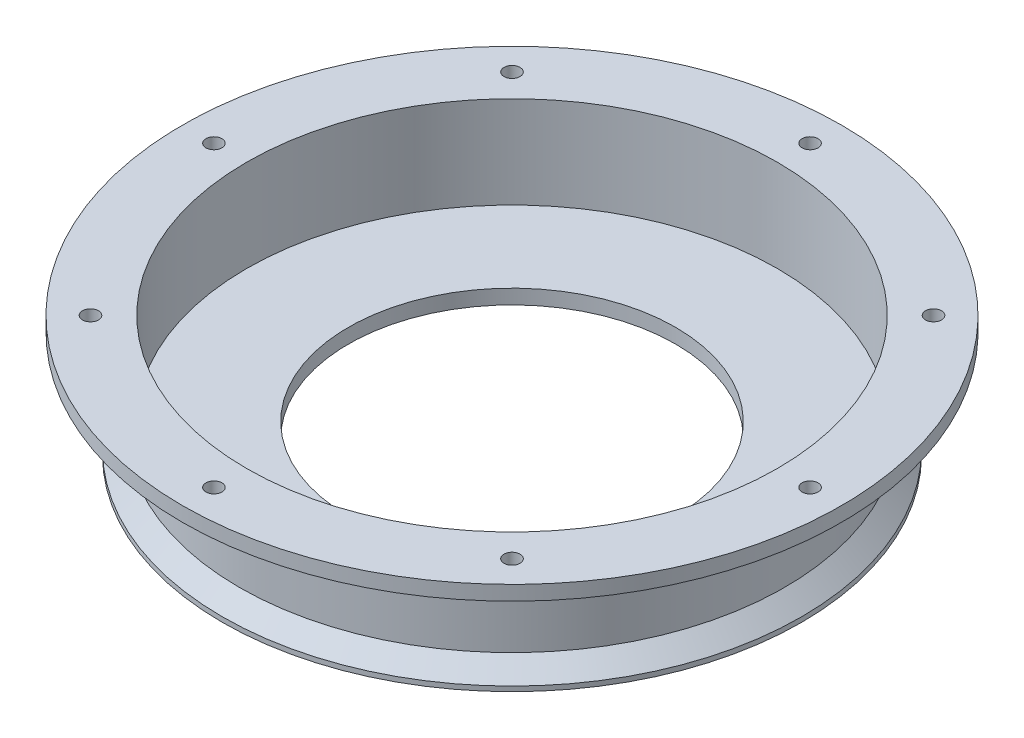
SolidWorks part; units mm, degrees
material "7050-T73510"
ref_plane "正面" through (0, 0, 0) normal (0, 0, 1) x (1, 0, 0)
ref_plane "平面" through (0, 0, 0) normal (0, 1, 0) x (1, 0, 0)
ref_plane "右側面" through (0, 0, 0) normal (1, 0, 0) x (0, 0, -1)
ref_axis "中心" through (0, 100.8172, 0) along (0, -1, 0)
sketch "ｽｹｯﾁ1" plane through (0, 0, 0) normal (0, 0, 1) x (1, 0, 0)
  line L0 (-109.5, 26.8454) -> (-136, 26.8454)
  line L1 (-136, 26.8454) -> (-136, 20.8454)
  line L2 (-136, 20.8454) -> (-112.5, 20.8454)
  line L3 (-112.5, 20.8454) -> (-112.5, -14.1546)
  line L4 (-112.5, -14.1546) -> (-119.5, -21.1546)
  line L5 (-119.5, -21.1546) -> (-119.5, -23.1546)
  line L6 (-119.5, -23.1546) -> (-110, -23.1546)
  line L7 (-110, -23.1546) -> (-104, -17.1546)
  line L8 (-104, -17.1546) -> (-67.5, -17.1546)
  line L9 (-67.5, -17.1546) -> (-67.5, -11.1546)
  line L10 (-67.5, -11.1546) -> (-109.5, -11.1546)
  line L11 (-109.5, -11.1546) -> (-109.5, 26.8454)
  line L13 (0, 35.1784) -> (0, -27.1557) construction
  dimension "D1" = 109.5
  dimension "D2" = 112.5
  dimension "D3" = 136
  dimension "D4" = 6
  dimension "D5" = 50
  dimension "D6" = 67.5
  dimension "D7" = 119.5
  dimension "D8" = 110
  dimension "D9" = 6
  dimension "D10" = 2
  dimension "D11" = 135
  dimension "D12" = 135
revolve "回転1" add sketch "ｽｹｯﾁ1" angle 360 about axis through (0, 100.8172, 0) along (0, -1, 0)
sketch "ｽｹｯﾁ2" plane through (0, 20.8454, 0) normal (0, -1, 0) x (1, 0, 0)
  circle A0 centre (123, 0) radius 3.3
  dimension "D1" = 6.6
  dimension "D2" = 123
extrude "Base_Plateへの固定用穴(M6の六角ボルトを使用)" cut sketch "ｽｹｯﾁ2" against normal through all
pattern_circular "円形ﾊﾟﾀｰﾝ1" count 8 over 360 about axis through (0, 0, 0) along (0, 1, 0) of "Base_Plateへの固定用穴(M6の六角ボルトを使用)"
sketch "ｽｹｯﾁ3" plane through (0, 20.8454, 0) normal (0, -1, 0) x (1, 0, 0)
  circle A0 centre (0, 123) radius 6
  dimension "D1" = 12
